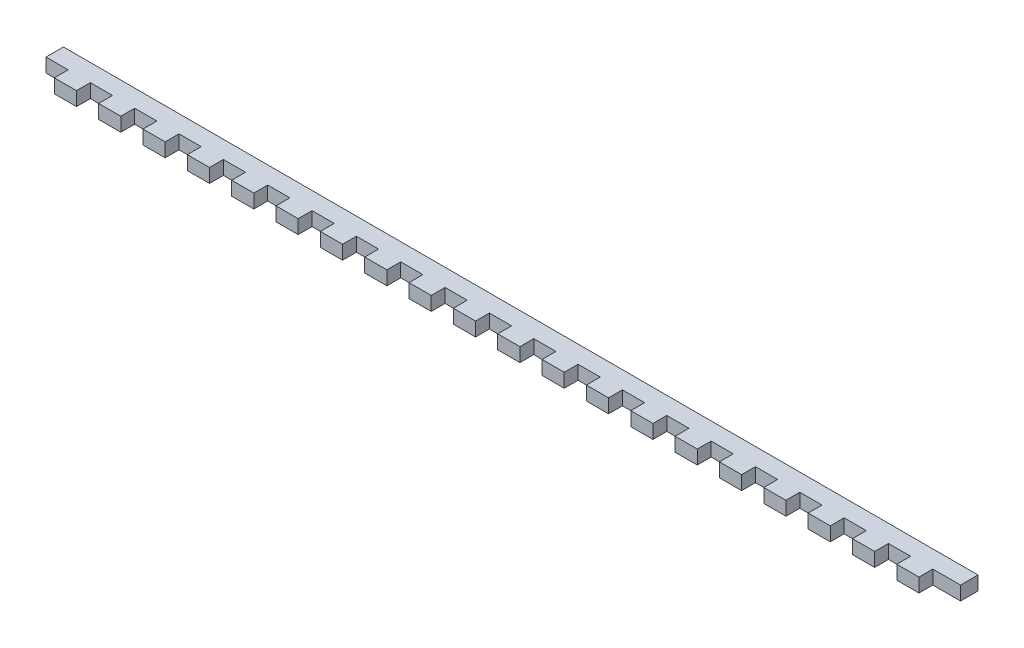
SolidWorks part; units mm, degrees
ref_plane "Front Plane" through (0, 0, 0) normal (0, 0, 1) x (1, 0, 0)
ref_plane "Top Plane" through (0, 0, 0) normal (0, 1, 0) x (1, 0, 0)
ref_plane "Right Plane" through (0, 0, 0) normal (1, 0, 0) x (0, 0, -1)
sketch "Sketch1" plane through (0, 0, 0) normal (0, 1, 0) x (1, 0, 0)
  line L0 (-139.4239, 2.0609) -> (-134.3439, 2.0609)
  line L1 (-139.4239, 6.0609) -> (70.1261, 6.0609)
  line L2 (-139.4239, 6.0609) -> (-139.4239, 2.0609)
  line L3 (-134.3439, -1.1141) -> (-129.2639, -1.1141)
  line L4 (70.1261, 6.0609) -> (70.1261, 2.0609)
  line L5 (-129.2639, 2.0609) -> (-129.2639, -1.1141)
  line L6 (-134.3439, 2.0609) -> (-134.3439, -1.1141)
  line L7 (-129.2639, 2.0609) -> (-124.1839, 2.0609)
  line L8 (-124.1839, -1.1141) -> (-119.1039, -1.1141)
  line L9 (-119.1039, 2.0609) -> (-119.1039, -1.1141)
  line L10 (-124.1839, 2.0609) -> (-124.1839, -1.1141)
  line L11 (-119.1039, 2.0609) -> (-114.0239, 2.0609)
  line L12 (-114.0239, -1.1141) -> (-108.9439, -1.1141)
  line L13 (-108.9439, 2.0609) -> (-108.9439, -1.1141)
  line L14 (-114.0239, 2.0609) -> (-114.0239, -1.1141)
  line L15 (-108.9439, 2.0609) -> (-103.8639, 2.0609)
  line L16 (-103.8639, -1.1141) -> (-98.7839, -1.1141)
  line L17 (-98.7839, 2.0609) -> (-98.7839, -1.1141)
  line L18 (-103.8639, 2.0609) -> (-103.8639, -1.1141)
  line L19 (-98.7839, 2.0609) -> (-93.7039, 2.0609)
  line L20 (-93.7039, -1.1141) -> (-88.6239, -1.1141)
  line L21 (-88.6239, 2.0609) -> (-88.6239, -1.1141)
  line L22 (-93.7039, 2.0609) -> (-93.7039, -1.1141)
  line L23 (-88.6239, 2.0609) -> (-83.5439, 2.0609)
  line L24 (-83.5439, -1.1141) -> (-78.4639, -1.1141)
  line L25 (-78.4639, 2.0609) -> (-78.4639, -1.1141)
  line L26 (-83.5439, 2.0609) -> (-83.5439, -1.1141)
  line L27 (-78.4639, 2.0609) -> (-73.3839, 2.0609)
  line L28 (-73.3839, -1.1141) -> (-68.3039, -1.1141)
  line L29 (-68.3039, 2.0609) -> (-68.3039, -1.1141)
  line L30 (-73.3839, 2.0609) -> (-73.3839, -1.1141)
  line L31 (-68.3039, 2.0609) -> (-63.2239, 2.0609)
  line L32 (-63.2239, -1.1141) -> (-58.1439, -1.1141)
  line L33 (-58.1439, 2.0609) -> (-58.1439, -1.1141)
  line L34 (-63.2239, 2.0609) -> (-63.2239, -1.1141)
  line L35 (-58.1439, 2.0609) -> (-53.0639, 2.0609)
  line L36 (-53.0639, -1.1141) -> (-47.9839, -1.1141)
  line L37 (-47.9839, 2.0609) -> (-47.9839, -1.1141)
  line L38 (-53.0639, 2.0609) -> (-53.0639, -1.1141)
  line L39 (-47.9839, 2.0609) -> (-42.9039, 2.0609)
  line L40 (-42.9039, -1.1141) -> (-37.8239, -1.1141)
  line L41 (-37.8239, 2.0609) -> (-37.8239, -1.1141)
  line L42 (-42.9039, 2.0609) -> (-42.9039, -1.1141)
  line L43 (-37.8239, 2.0609) -> (-32.7439, 2.0609)
  line L44 (-32.7439, -1.1141) -> (-27.6639, -1.1141)
  line L45 (-27.6639, 2.0609) -> (-27.6639, -1.1141)
  line L46 (-32.7439, 2.0609) -> (-32.7439, -1.1141)
  line L47 (-27.6639, 2.0609) -> (-22.5839, 2.0609)
  line L48 (-22.5839, -1.1141) -> (-17.5039, -1.1141)
  line L49 (-17.5039, 2.0609) -> (-17.5039, -1.1141)
  line L50 (-22.5839, 2.0609) -> (-22.5839, -1.1141)
  line L51 (-17.5039, 2.0609) -> (-12.4239, 2.0609)
  line L52 (-12.4239, -1.1141) -> (-7.3439, -1.1141)
  line L53 (-7.3439, 2.0609) -> (-7.3439, -1.1141)
  line L54 (-12.4239, 2.0609) -> (-12.4239, -1.1141)
  line L55 (-7.3439, 2.0609) -> (-2.2639, 2.0609)
  line L56 (-2.2639, -1.1141) -> (2.8161, -1.1141)
  line L57 (2.8161, 2.0609) -> (2.8161, -1.1141)
  line L58 (-2.2639, 2.0609) -> (-2.2639, -1.1141)
  line L59 (2.8161, 2.0609) -> (7.8961, 2.0609)
  line L60 (7.8961, -1.1141) -> (12.9761, -1.1141)
  line L61 (12.9761, 2.0609) -> (12.9761, -1.1141)
  line L62 (7.8961, 2.0609) -> (7.8961, -1.1141)
  line L63 (12.9761, 2.0609) -> (18.0561, 2.0609)
  line L64 (18.0561, -1.1141) -> (23.1361, -1.1141)
  line L65 (23.1361, 2.0609) -> (23.1361, -1.1141)
  line L66 (18.0561, 2.0609) -> (18.0561, -1.1141)
  line L67 (23.1361, 2.0609) -> (28.2161, 2.0609)
  line L68 (28.2161, -1.1141) -> (33.2961, -1.1141)
  line L69 (33.2961, 2.0609) -> (33.2961, -1.1141)
  line L70 (28.2161, 2.0609) -> (28.2161, -1.1141)
  line L71 (33.2961, 2.0609) -> (38.3761, 2.0609)
  line L72 (38.3761, -1.1141) -> (43.4561, -1.1141)
  line L73 (43.4561, 2.0609) -> (43.4561, -1.1141)
  line L74 (38.3761, 2.0609) -> (38.3761, -1.1141)
  line L75 (43.4561, 2.0609) -> (48.5361, 2.0609)
  line L76 (48.5361, -1.1141) -> (53.6161, -1.1141)
  line L77 (53.6161, 2.0609) -> (53.6161, -1.1141)
  line L78 (48.5361, 2.0609) -> (48.5361, -1.1141)
  line L79 (53.6161, 2.0609) -> (58.6961, 2.0609)
  line L80 (58.6961, -1.1141) -> (63.7761, -1.1141)
  line L81 (63.7761, 2.0609) -> (63.7761, -1.1141)
  line L82 (58.6961, 2.0609) -> (58.6961, -1.1141)
  line L84 (63.7761, 2.0609) -> (70.1261, 2.0609)
  dimension "D1" = 209.55
  dimension "D2" = 4
  dimension "D3" = 5.08
  dimension "D4" = 10.16
  dimension "D5" = 3.175
  dimension "D6" = 20
extrude "Boss-Extrude1" add sketch "Sketch1" along normal blind 3.175
sketch "Sketch2" plane through (0, 0, 0) normal (0, -1, 0) x (1, 0, 0)
